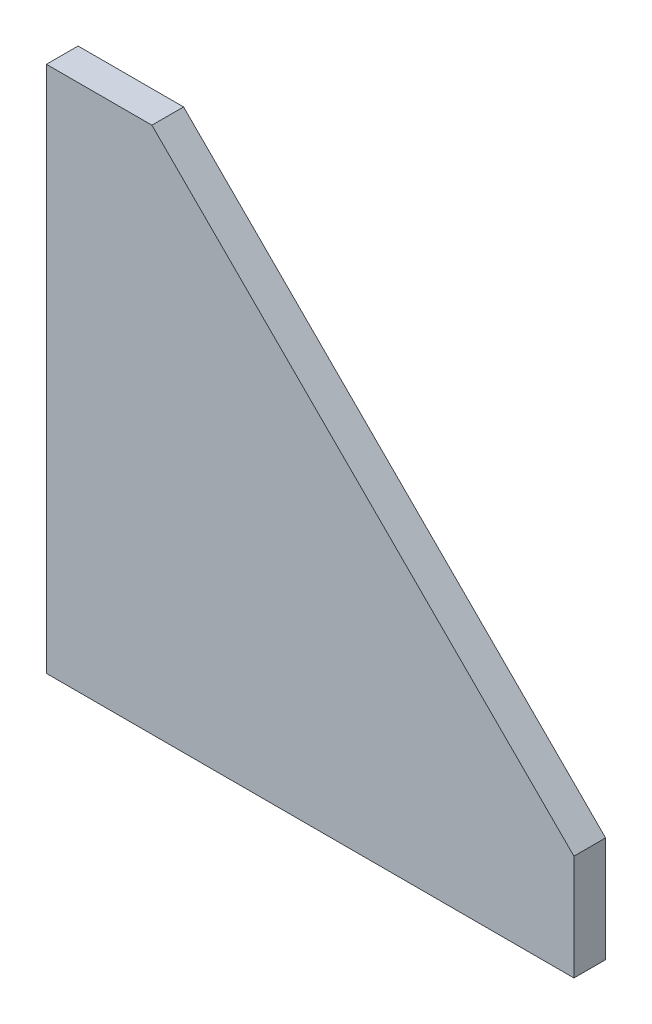
SolidWorks part; units mm, degrees
ref_plane "前视基准面" through (0, 0, 0) normal (0, 0, 1) x (1, 0, 0)
ref_plane "上视基准面" through (0, 0, 0) normal (0, 1, 0) x (1, 0, 0)
ref_plane "右视基准面" through (0, 0, 0) normal (1, 0, 0) x (0, 0, -1)
sketch "草图1" plane through (0, 0, 0) normal (0, 0, 1) x (1, 0, 0)
  line L0 (0, 0) -> (0, 50)
  line L1 (0, -55) -> (0, 55) construction
  line L2 (0, 50) -> (10, 50)
  line L3 (10, 50) -> (50, 10)
  line L4 (50, 10) -> (50, 0)
  line L5 (55, 0) -> (-55, 0) construction
  line L6 (50, 0) -> (0, 0)
  line L8 (-6.298, 0) -> (0, -6.298) construction
  dimension "D1" = 50
  dimension "D2" = 10
extrude "凸台-拉伸1" add sketch "草图1" along normal blind 3
